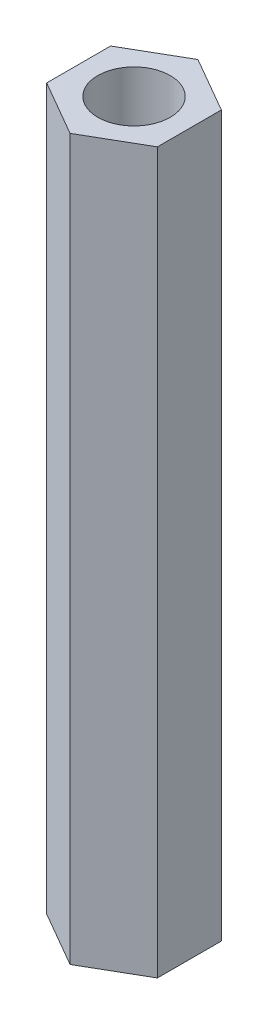
SolidWorks part; units mm, degrees
ref_plane "Front Plane" through (0, 0, 0) normal (0, 0, 1) x (1, 0, 0)
ref_plane "Top Plane" through (0, 0, 0) normal (0, 1, 0) x (1, 0, 0)
ref_plane "Right Plane" through (0, 0, 0) normal (1, 0, 0) x (0, 0, -1)
sketch "Sketch1" plane through (0, 0, 0) normal (0, 1, 0) x (1, 0, 0)
  line L0 (2.5002, 1.4435) -> (2.5002, -1.4435)
  line L1 (2.5002, -1.4435) -> (0, -2.887)
  line L2 (0, -2.887) -> (-2.5002, -1.4435)
  line L3 (-2.5002, -1.4435) -> (-2.5002, 1.4435)
  line L4 (-2.5002, 1.4435) -> (0, 2.887)
  line L5 (0, 2.887) -> (2.5002, 1.4435)
  circle A0 centre (0, 0) radius 1.635
  dimension "D1" = 3.27
  dimension "D3" = 2.887
  dimension "D4" = 2.887
  dimension "D5" = 2.887
  dimension "D6" = 2.887
  dimension "D7" = 2.887
extrude "Boss-Extrude1" add sketch "Sketch1" along normal blind 32.5
